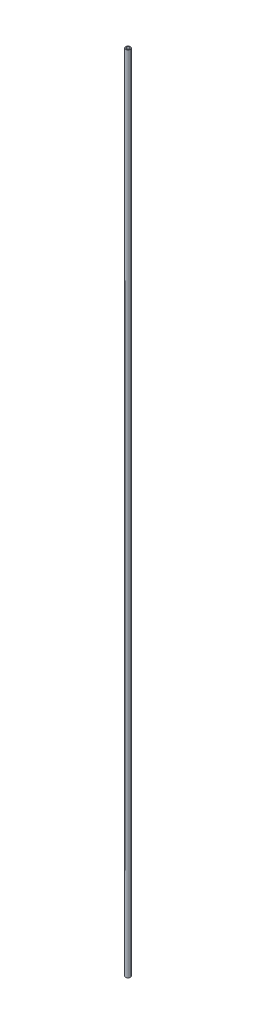
SolidWorks part; units mm, degrees
ref_plane "前视基准面" through (0, 0, 0) normal (0, 0, 1) x (1, 0, 0)
ref_plane "上视基准面" through (0, 0, 0) normal (0, 1, 0) x (1, 0, 0)
ref_plane "右视基准面" through (0, 0, 0) normal (1, 0, 0) x (0, 0, -1)
sketch "草图1" plane through (0, 0, 0) normal (0, 1, 0) x (1, 0, 0)
  circle A0 centre (0, 0) radius 0.6
  dimension "D1" = 1.2
extrude "凸台-拉伸1" add sketch "草图1" along normal blind 200
sketch "草图2" plane through (0, 0, 0) normal (0, -1, 0) x (1, 0, 0)
  circle A0 centre (0, 0) radius 0.4
  dimension "D1" = 0.8
extrude "切除-拉伸1" cut sketch "草图2" against normal through all
